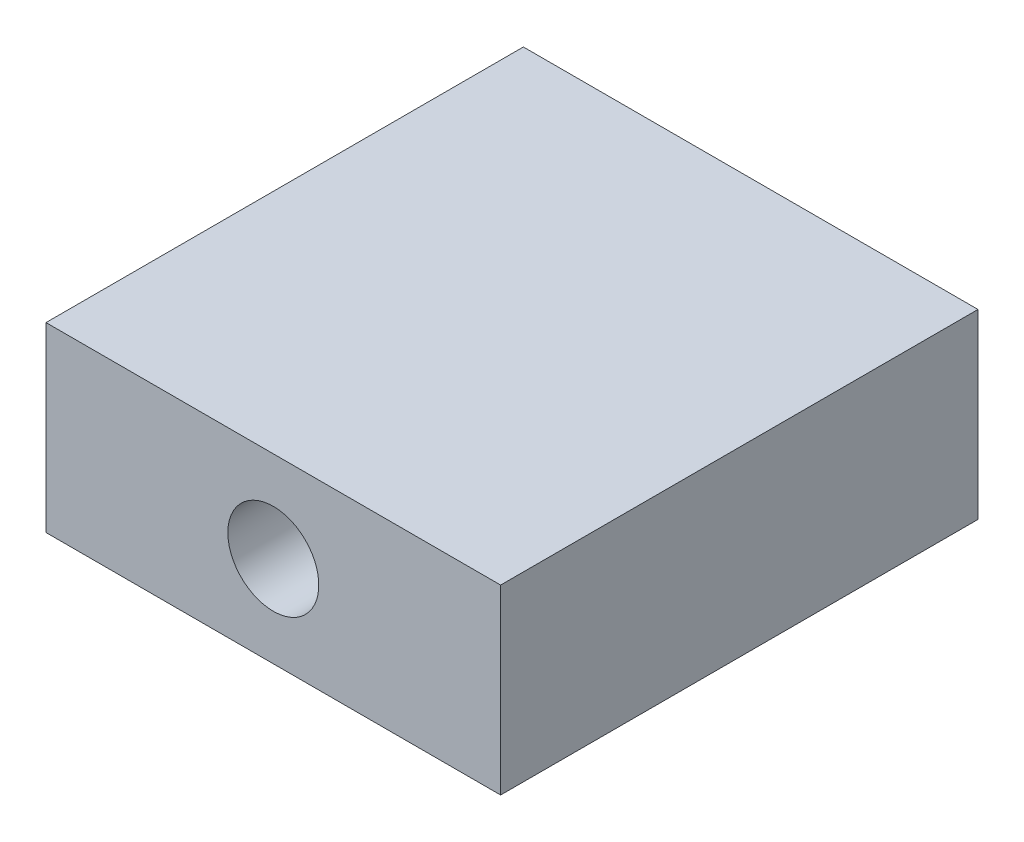
SolidWorks part; units mm, degrees
ref_plane "Front Plane" through (0, 0, 0) normal (0, 0, 1) x (1, 0, 0)
ref_plane "Top Plane" through (0, 0, 0) normal (0, 1, 0) x (1, 0, 0)
ref_plane "Right Plane" through (0, 0, 0) normal (1, 0, 0) x (0, 0, -1)
sketch "Sketch1" plane through (0, 0, 0) normal (0, 0, 1) x (1, 0, 0)
  line L1 (0, 0) -> (20, 0)
  line L2 (0, 0) -> (0, -8)
  line L3 (0, -8) -> (20, -8)
  line L4 (20, 0) -> (20, -8)
  circle A0 centre (10, -4) radius 2
  point P8 (10, -8)
  point P9 (0, -4)
  dimension "D3" = 4
  dimension "D1" = 8
  dimension "D2" = 20
extrude "Boss-Extrude1" add sketch "Sketch1" along normal blind 21
